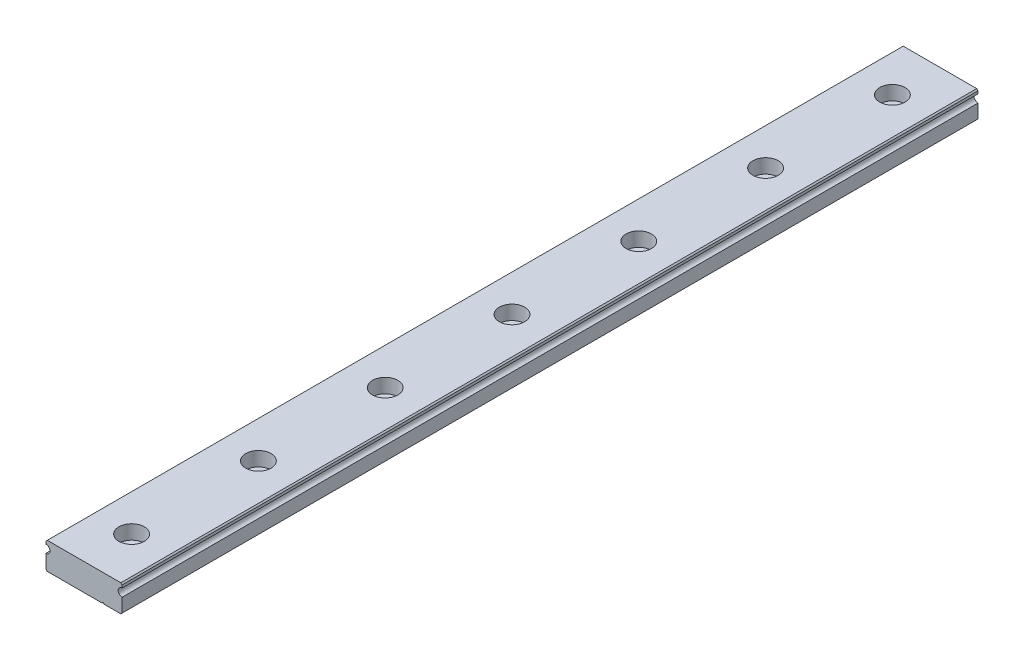
SolidWorks part; units mm, degrees
material "45#"
ref_plane "前视" through (0, 0, 0) normal (0, 0, 1) x (1, 0, 0)
ref_plane "上视" through (0, 0, 0) normal (0, 1, 0) x (1, 0, 0)
ref_plane "右视" through (0, 0, 0) normal (1, 0, 0) x (0, 0, -1)
sketch "草图1" plane through (0, 0, 0) normal (0, 0, 1) x (1, 0, 0)
  line L0 (0, 4.25) -> (0, -4.25) construction
  line L1 (-12, 3) -> (-12, 3.85)
  line L2 (-11.6, 4.25) -> (-12, 3.85)
  line L3 (11.6, 4.25) -> (-11.6, 4.25)
  line L4 (12, 3.85) -> (11.6, 4.25)
  line L5 (12, 3.85) -> (12, 3)
  line L6 (11.6, -4.25) -> (12, -3.85)
  line L7 (11.6, -4.25) -> (6.3, -4.25)
  line L8 (5.7, -4.25) -> (-11.6, -4.25)
  line L9 (-12, -3.85) -> (-11.6, -4.25)
  line L10 (-12, -3.85) -> (-12, 0.5)
  line L11 (12, 0.5) -> (12, -3.85)
  arc A0 (-12, 0.5) -> (-12, 3) centre (-12, 1.75) ccw
  arc A1 (12, 3) -> (12, 0.5) centre (12, 1.75) ccw
  arc A2 (6.3, -4.25) -> (5.7, -4.25) centre (6, -4.25) ccw
extrude "凸台-拉伸1" add sketch "草图1" against normal blind 270
hole_wizard "打孔尺寸根据内六角圆柱头螺钉的类型1" positions "草图3" profile "草图2" counterbore size "M4" standard "Gb" end condition through all
sketch "草图3" plane through (0, 4.25, 0) normal (0, 1, 0) x (1, 0, 0)
  line L0 (0, 270) -> (0, 0) construction
  line L1 (11.6, 270) -> (-11.6, 270) construction
  line L2 (11.6, 0) -> (-11.6, 0) construction
  point P0 (0, 15)
  dimension "D1" = 15
sketch "草图2" plane through (0, 4.25, -15) normal (1, 0, 0) x (0, 0, 1)
  line L0 (0, 0) -> (0, 8.5)
  line L1 (0, 8.5) -> (2.25, 8.5)
  line L3 (2.25, 8.5) -> (2.25, 4.5)
  line L4 (2.25, 4.5) -> (4, 4.5)
  line L5 (4, 4.5) -> (4, 0)
  line L7 (4, 0) -> (0, 0)
  line L11 (0, -6.35) -> (0, 107.95) construction
  dimension "通孔孔直径" = 4.5
  dimension "通孔孔深度" = 8.5
  dimension "柱形沉头孔直径" = 8
  dimension "柱形沉头孔深度" = 4.5
pattern_linear "阵列(线性)1" count 7 spacing 40 along (0, 0, -1) of "打孔尺寸根据内六角圆柱头螺钉的类型1"
